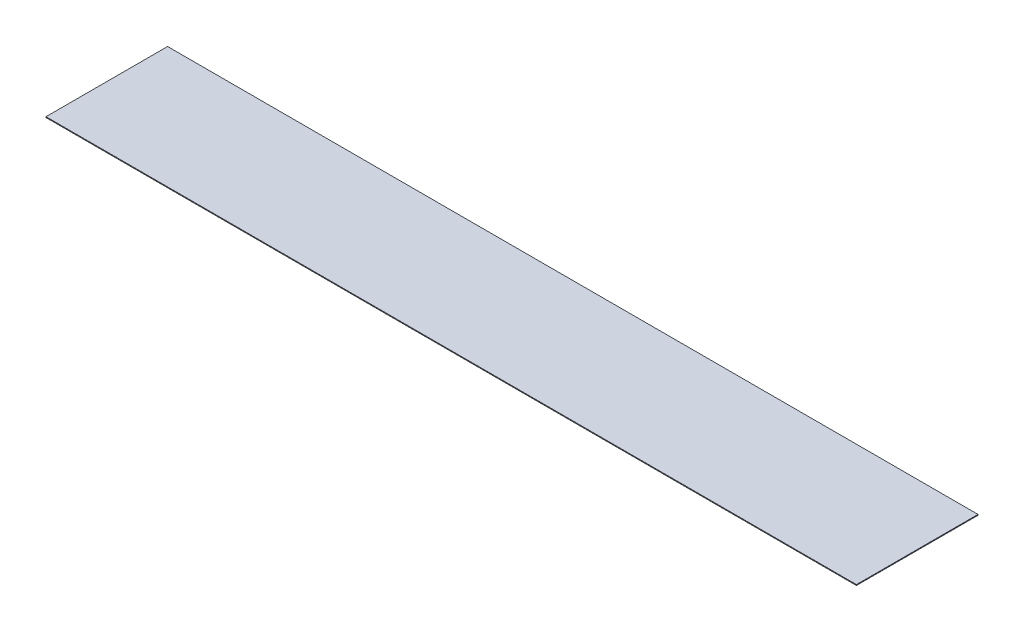
SolidWorks part; units mm, degrees
ref_plane "前视基准面" through (0, 0, 0) normal (0, 0, 1) x (1, 0, 0)
ref_plane "上视基准面" through (0, 0, 0) normal (0, 1, 0) x (1, 0, 0)
ref_plane "右视基准面" through (0, 0, 0) normal (1, 0, 0) x (0, 0, -1)
sketch "草图1" plane through (0, 0, 0) normal (0, 1, 0) x (1, 0, 0)
  line L1 (-500, -75) -> (500, -75)
  line L2 (-500, -75) -> (-500, 75)
  line L3 (-500, 75) -> (500, 75)
  line L4 (500, -75) -> (500, 75)
  line L5 (-500, -75) -> (500, 75) construction
  line L6 (-500, 75) -> (500, -75) construction
  point P0 (0, 0)
  dimension "D1" = 1000
  dimension "D2" = 150
extrude "凸台-拉伸1" add sketch "草图1" along normal blind 1
